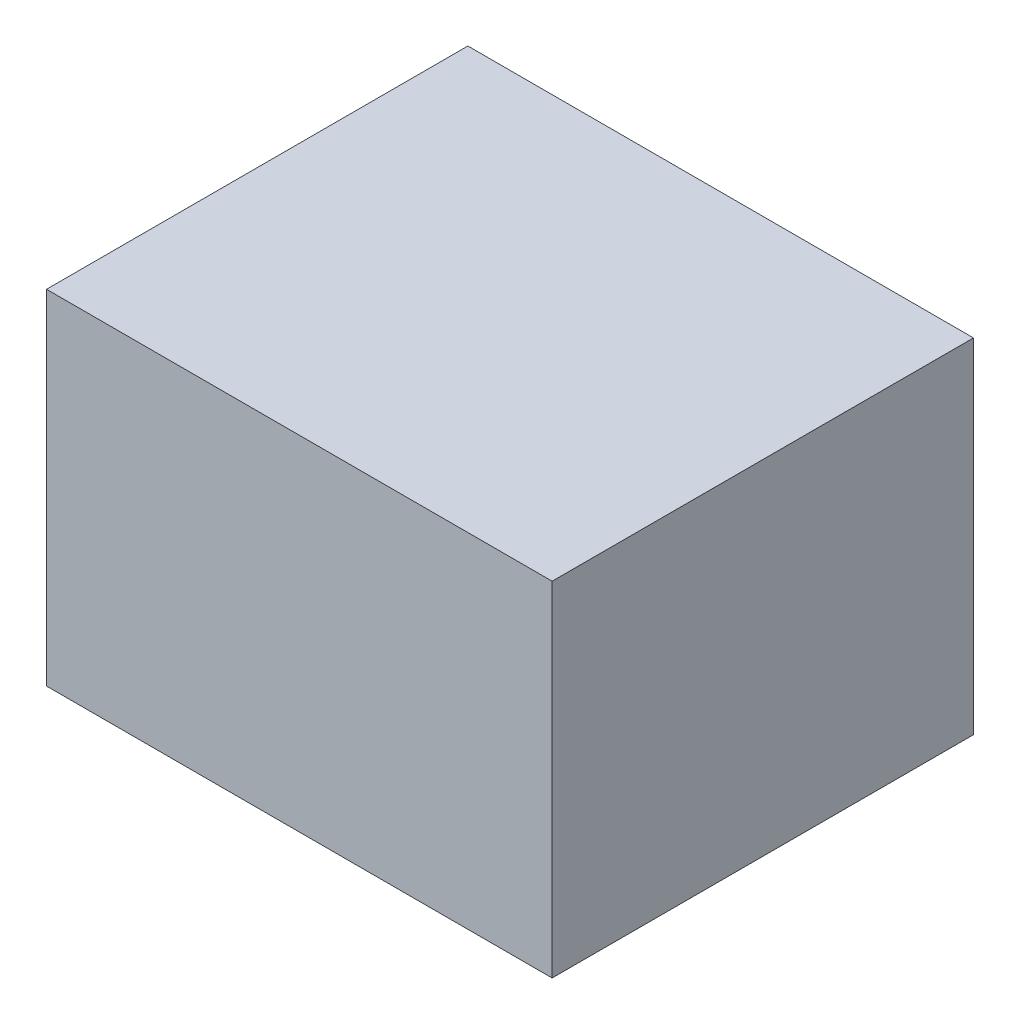
SolidWorks part; units mm, degrees
material "Chrome Stainless Steel"
ref_plane "Front Plane" through (0, 0, 0) normal (0, 0, 1) x (1, 0, 0)
ref_plane "Top Plane" through (0, 0, 0) normal (0, 1, 0) x (1, 0, 0)
ref_plane "Right Plane" through (0, 0, 0) normal (1, 0, 0) x (0, 0, -1)
sketch "Sketch1" plane through (0, 0, 0) normal (0, 0, 1) x (1, 0, 0)
  line L1 (0, 0) -> (72.39, 0)
  line L2 (0, 0) -> (0, 49.1998)
  line L3 (0, 49.1998) -> (72.39, 49.1998)
  line L4 (72.39, 0) -> (72.39, 49.1998)
  dimension "D1" = 72.39
  dimension "D2" = 49.1998
extrude "Boss-Extrude1" add sketch "Sketch1" along normal blind 60.325
